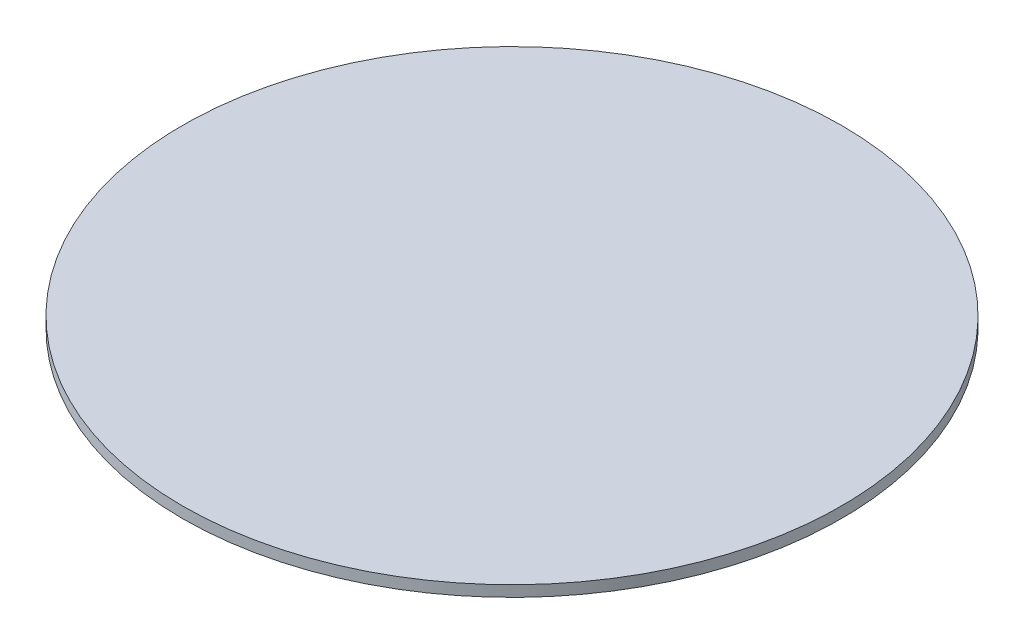
SolidWorks part; units mm, degrees
ref_plane "前视基准面" through (0, 0, 0) normal (0, 0, 1) x (1, 0, 0)
ref_plane "上视基准面" through (0, 0, 0) normal (0, 1, 0) x (1, 0, 0)
ref_plane "右视基准面" through (0, 0, 0) normal (1, 0, 0) x (0, 0, -1)
sketch "草图1" plane through (0, 0, 0) normal (0, 1, 0) x (1, 0, 0)
  circle A0 centre (0, 0) radius 6
  dimension "D1" = 12
extrude "凸台-拉伸1" add sketch "草图1" along normal blind 0.2
